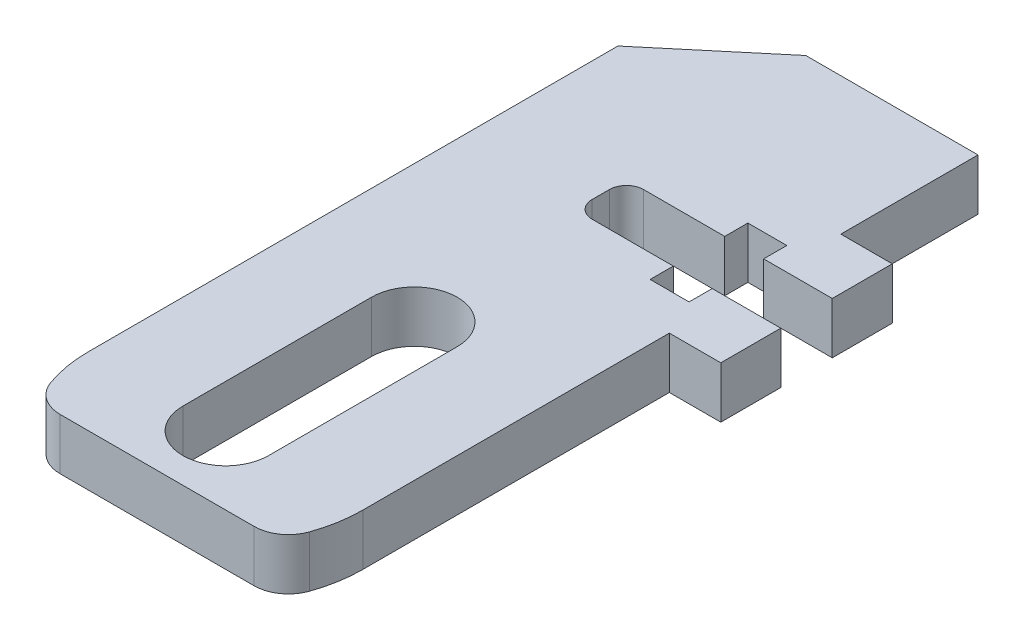
SolidWorks part; units mm, degrees
material "Acrylic (Medium-high impact)"
ref_plane "Plano frontal" through (0, 0, 0) normal (0, 0, 1) x (1, 0, 0)
ref_plane "Plano superior" through (0, 0, 0) normal (0, 1, 0) x (1, 0, 0)
ref_plane "Plano direito" through (0, 0, 0) normal (1, 0, 0) x (0, 0, -1)
sketch "Sketch2" plane through (0, 0, 0) normal (0, 1, 0) x (1, 0, 0)
  line L0 (-8, 10.7486) -> (-8, 30.8702)
  line L2 (-8, 10.7486) -> (-8, 0)
  line L4 (8, 10.7486) -> (8, 0)
  line L6 (-8, 30.8702) -> (8, 30.8702) construction
  line L9 (8, 30.8702) -> (8, 27.8702)
  line L10 (8, 17.8702) -> (8, 14.8702)
  line L11 (8, 27.8702) -> (11, 27.8702)
  line L13 (8, 17.8702) -> (11, 17.8702)
  line L14 (11, 27.8702) -> (11, 17.8702)
  line L15 (-8, 10.7486) -> (8, 10.7486) construction
  line L17 (8, 14.8702) -> (8, 10.7486)
  line L18 (-8, 30.8702) -> (-2.0412, 35.8702)
  line L19 (-2.0412, 35.8702) -> (8, 35.8702)
  line L20 (8, 35.8702) -> (8, 30.8702)
  line L21 (0, 0) -> (0, 11) construction
  line L22 (-2.5, 0) -> (-2.5, 11)
  line L23 (2.5, 0) -> (2.5, 11)
  line L24 (-5.6569, -4) -> (5.6569, -4)
  circle A0 centre (0, 0) radius 15 construction
  arc A1 (-8, 0) -> (-7.5425, -2.6667) centre (0, 0) ccw
  circle A2 centre (0, 0) radius 2.5 construction
  arc A3 (-2.5, 0) -> (2.5, 0) centre (0, 0) ccw
  arc A4 (2.5, 11) -> (-2.5, 11) centre (0, 11) ccw
  arc A5 (7.5425, -2.6667) -> (8, 0) centre (0, 0) ccw
  arc A6 (-6.9282, -4) -> (6.9282, -4) centre (0, 0) ccw construction
  arc A7 (5.6569, -4) -> (7.5425, -2.6667) centre (5.6569, -2) ccw
  arc A8 (-5.6569, -4) -> (-7.5425, -2.6667) centre (-5.6569, -2) cw
  point P12 (0, 5.5)
  dimension "D1" = 30
  dimension "D2" = 5
  dimension "D3" = 10.7486
  dimension "D4" = 5
  dimension "D11" = 10.0412
  dimension "D10" = 8
  dimension "D9" = 35.8702
  dimension "D14" = 2
  dimension "D15" = 11
  dimension "D5" = 3
  dimension "D6" = 10
  dimension "D7" = 3
  dimension "D8" = 40
  dimension "D12" = 1.5
  dimension "D13" = 11
extrude "Boss-Extrude1" add sketch "Sketch2" along normal mid plane 3
sketch "Sketch4" plane through (0, 0, 0) normal (0, 1, 0) x (1, 0, 0)
  line L0 (11, 17.8702) -> (11, 27.8702) construction
  line L1 (11, 24.3702) -> (7, 24.3702)
  line L2 (11, 24.3702) -> (11, 21.3702)
  line L3 (11, 21.3702) -> (7, 21.3702)
  line L4 (-1, 23.3702) -> (-1, 22.3702)
  line L6 (4.73, 24.3702) -> (0, 24.3702)
  line L7 (4.73, 25.7202) -> (7, 25.7202)
  line L8 (4.73, 25.7202) -> (4.73, 24.3702)
  line L9 (4.73, 20.0202) -> (7, 20.0202)
  line L10 (7, 25.7202) -> (7, 24.3702)
  line L11 (4.73, 21.3702) -> (4.73, 20.0202)
  line L12 (7, 21.3702) -> (7, 20.0202)
  line L13 (4.73, 21.3702) -> (0, 21.3702)
  line L14 (11, 27.8702) -> (8, 27.8702) construction
  arc A0 (0, 21.3702) -> (-1, 22.3702) centre (0, 22.3702) cw
  arc A1 (0, 24.3702) -> (-1, 23.3702) centre (0, 23.3702) ccw
  arc A2 (2.5, 11) -> (-2.5, 11) centre (0, 11) ccw construction
  point P6 (11, 22.8702)
  point P17 (-1, 21.3702)
  point P20 (-1, 24.3702)
  dimension "D7" = 1
  dimension "D9" = 7.8702
  dimension "D10" = 6.5202
  dimension "D1" = 12
  dimension "D2" = 3
  dimension "D3" = 2.27
  dimension "D4" = 1.35
  dimension "D5" = 1.35
  dimension "D6" = 4
  dimension "D8" = 3.5
extrude "Cut-Extrude1" cut sketch "Sketch4" against normal through all both and the other way through all
sketch "Sketch3" plane through (0, 0, 0) normal (0, 1, 0) x (1, 0, 0)
  circle A0 centre (0, 0) radius 15
  circle A1 centre (0, 11) radius 15 construction
  dimension "D1" = 30
